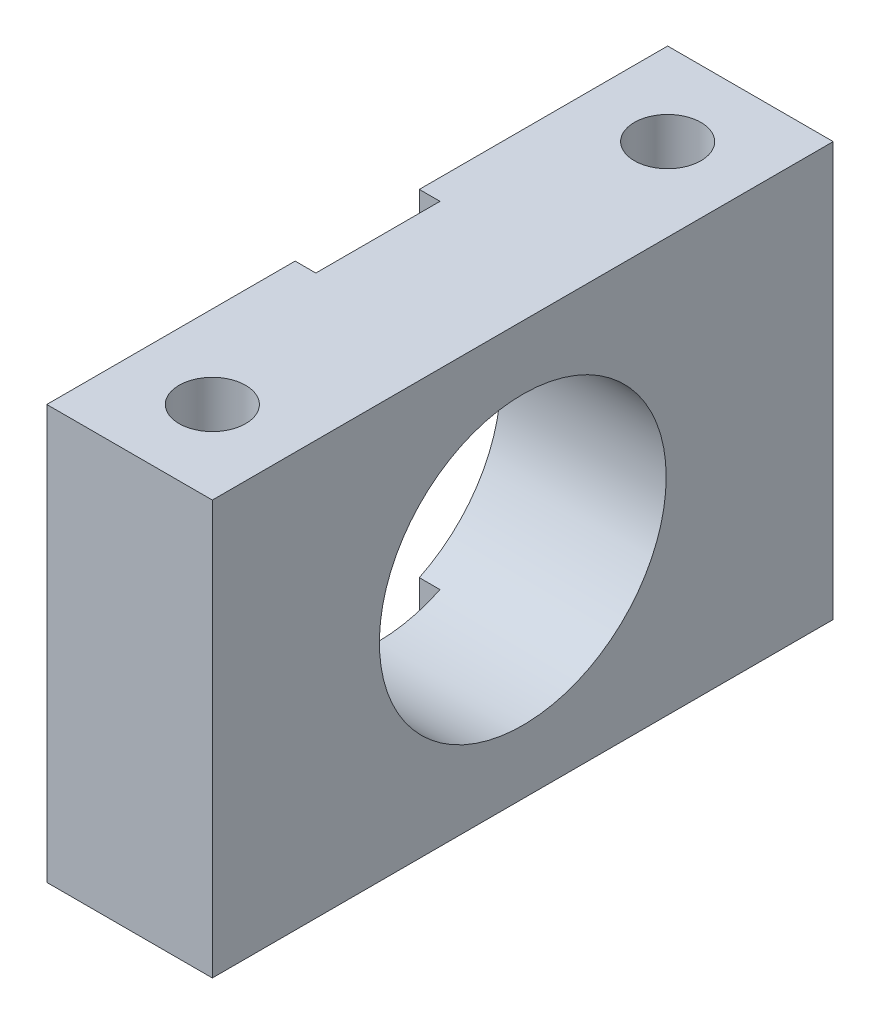
SolidWorks part; units mm, degrees
material "6063-T6"
ref_plane "Front Plane" through (0, 0, 0) normal (0, 0, 1) x (1, 0, 0)
ref_plane "Top Plane" through (0, 0, 0) normal (0, 1, 0) x (1, 0, 0)
ref_plane "Right Plane" through (0, 0, 0) normal (1, 0, 0) x (0, 0, -1)
sketch "Sketch1" plane through (0, 0, 0) normal (1, 0, 0) x (0, 0, -1)
  line L1 (23.8125, -15.875) -> (-23.8125, -15.875)
  line L2 (23.8125, -15.875) -> (23.8125, 15.875)
  line L3 (23.8125, 15.875) -> (-23.8125, 15.875)
  line L4 (-23.8125, -15.875) -> (-23.8125, 15.875)
  line L5 (23.8125, -15.875) -> (-23.8125, 15.875) construction
  line L6 (23.8125, 15.875) -> (-23.8125, -15.875) construction
  circle A0 centre (0, 0) radius 11
  dimension "D1" = 22
  dimension "D2" = 31.75
  dimension "D3" = 47.625
extrude "Boss-Extrude1" add sketch "Sketch1" along normal mid plane 12.7
sketch "Sketch3" plane through (0, -15.875, 0) normal (0, -1, 0) x (1, 0, 0)
  line L0 (6.35, 23.8125) -> (-6.35, 23.8125) construction
  line L1 (-6.35, 23.8125) -> (-6.35, -23.8125) construction
  circle A0 centre (0, 17.4625) radius 2.5527
  dimension "D1" = 6.35
  dimension "D3" = 5.1054
  dimension "D2" = 6.35
extrude "Cut-Extrude2" cut sketch "Sketch3" against normal through all
mirror "Mirror1" about plane through (0, 0, 0) normal (0, 0, 1) of "Cut-Extrude2"
sketch "Sketch4" plane through (-6.35, 0, 0) normal (-1, 0, 0) x (0, 0, 1)
  line L1 (4.7625, -17.8246) -> (-4.7625, -17.8246)
  line L2 (4.7625, -17.8246) -> (4.7625, 17.8246)
  line L3 (4.7625, 17.8246) -> (-4.7625, 17.8246)
  line L4 (-4.7625, -17.8246) -> (-4.7625, 17.8246)
  line L5 (4.7625, -17.8246) -> (-4.7625, 17.8246) construction
  line L6 (4.7625, 17.8246) -> (-4.7625, -17.8246) construction
  point P0 (0, 0)
  dimension "D1" = 9.525
extrude "Cut-Extrude3" cut sketch "Sketch4" against normal blind 1.5875
